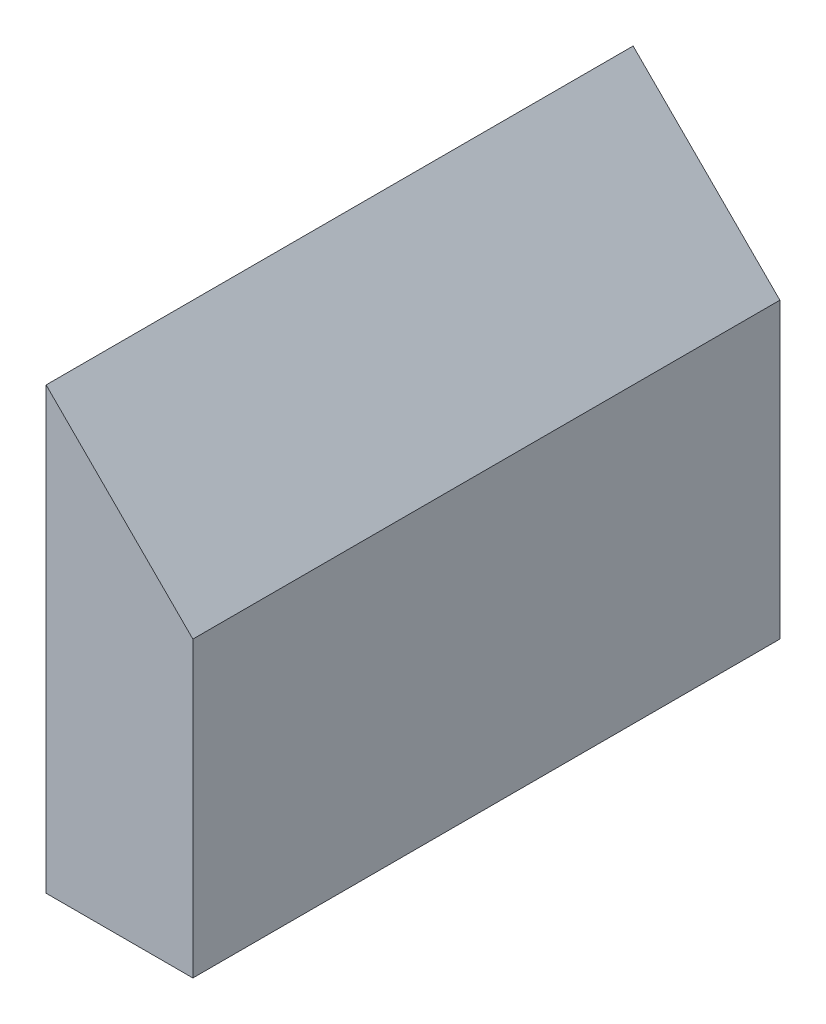
SolidWorks part; units mm, degrees
ref_plane "Front Plane" through (0, 0, 0) normal (0, 0, 1) x (1, 0, 0)
ref_plane "Top Plane" through (0, 0, 0) normal (0, 1, 0) x (1, 0, 0)
ref_plane "Right Plane" through (0, 0, 0) normal (1, 0, 0) x (0, 0, -1)
sketch "Sketch3" plane through (0, 0, 0) normal (0, 0, 1) x (1, 0, 0)
  line L0 (0, 0) -> (0, 30)
  line L1 (0, 30) -> (10, 20)
  line L2 (10, 20) -> (10, 0)
  line L3 (10, 0) -> (0, 0)
  dimension "D1" = 30
  dimension "D2" = 20
  dimension "D3" = 10
extrude "Boss-Extrude1" add sketch "Sketch3" along normal blind 40 contours L1 L2 L3 L0
